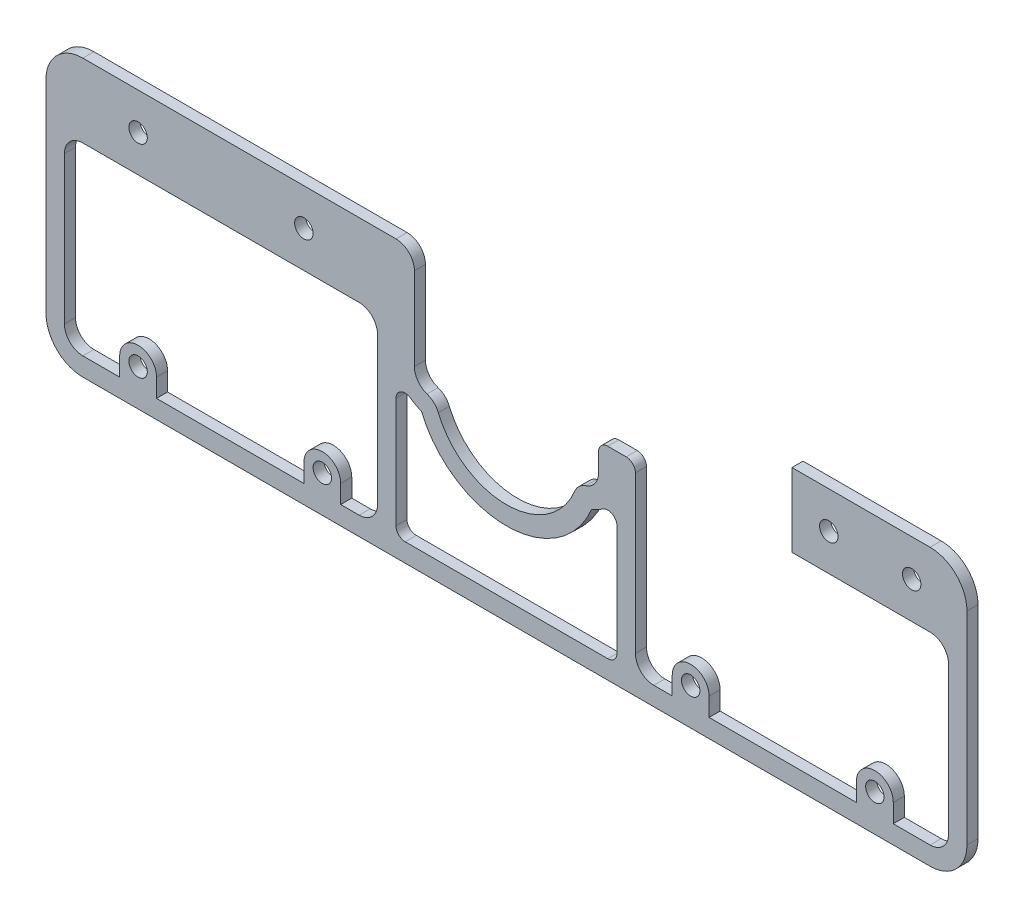
SolidWorks part; units mm, degrees
ref_plane "Front Plane" through (0, 0, 0) normal (0, 0, 1) x (1, 0, 0)
ref_plane "Top Plane" through (0, 0, 0) normal (0, 1, 0) x (1, 0, 0)
ref_plane "Right Plane" through (0, 0, 0) normal (1, 0, 0) x (0, 0, -1)
sketch "Sketch1" plane through (0, 0, 0) normal (0, 0, 1) x (1, 0, 0)
  line L0 (-40, 20) -> (-40, 55) construction
  line L4 (-250, -55) -> (-250, 3.1783)
  line L8 (-50, 75) -> (-230, 75) construction
  line L17 (0, -20) -> (0, -40)
  line L25 (0, -65) -> (0, -75)
  line L26 (0, 75) -> (0, -75) construction
  line L27 (-50, 95) -> (50, 95) construction
  line L34 (0, -75) -> (-230, -75)
  line L156 (-50, 75) -> (-230, 75) construction
  line L161 (0, -40) -> (0, -65)
  line L165 (-164.3309, 75) -> (-60, 75)
  line L167 (-230, 75) -> (-220, 75)
  line L171 (-250, 3.1783) -> (-250, 55)
  line L172 (-220, 75) -> (-164.3309, 75)
  line L173 (-50, 65) -> (-50, 20)
  arc A0 (-40, 20) -> (0, -20) centre (0, 20) ccw construction
  circle A1 centre (0, 20) radius 30 construction
  arc A4 (-230, -75) -> (-250, -55) centre (-230, -55) cw
  arc A5 (-250, 55) -> (-230, 75) centre (-230, 55) cw
  arc A124 (0, -20) -> (-37, 4.8013) centre (0, 20) cw
  arc A125 (-60, 75) -> (-50, 65) centre (-60, 65) cw
  arc A126 (-43.125, 10.5008) -> (-50, 20) centre (-40, 20) cw
  arc A127 (-37, 4.8013) -> (-43.125, 10.5008) centre (-46.25, 1.0016) ccw
  point P0 (0, 0)
  point P10 (-50, 10)
  point P11 (0, 50)
  point P30 (-40, 75)
  point P45 (0, -30)
  point P74 (0, 95)
  dimension "D3" = 80
  dimension "D4" = 60
  dimension "D6" = 55
  dimension "D7" = 75
  dimension "D10" = 10
  dimension "D11" = 20
  dimension "D8" = 10
  dimension "D5" = 10
  dimension "D9" = 20
  dimension "D13" = 210
  dimension "D16" = 100
  dimension "D17" = 20
  dimension "D26" = 250
extrude "Boss-Extrude1" add sketch "Sketch1" along normal blind 6
mirror "Mirror1" about plane through (0, -20, 6) normal (-1, 0, 0) of "Boss-Extrude1"
sketch "Sketch3" plane through (0, 0, 6) normal (0, 0, 1) x (1, 0, 0)
  line L0 (155, 75) -> (155, 35)
  line L1 (60, 75) -> (230, 75) construction
  line L2 (155, 35) -> (50, 35)
  line L3 (50, 20) -> (50, 65) construction
  line L4 (50, 20) -> (50, 65) construction
  line L5 (60, 75) -> (230, 75)
  line L6 (50, 65) -> (50, 35)
  line L7 (-60, 75) -> (-230, 75) construction
  line L8 (-250, 55) -> (-250, -55) construction
  line L9 (250, 55) -> (250, -55) construction
  arc A0 (60, 75) -> (50, 65) centre (60, 65) ccw construction
  arc A1 (60, 75) -> (50, 65) centre (60, 65) ccw
  circle A2 centre (175, 55) radius 5
  circle A3 centre (220, 55) radius 5
  circle A4 centre (-200, 55) radius 5
  circle A5 centre (-110, 55) radius 5
  line M15 (230, 75) -> (60, 75)
  arc M16 (60, 75) -> (50, 65) centre (60, 65) ccw
  line M17 (50, 65) -> (50, 20)
  dimension "D3" = 10
  dimension "D4" = 10
  dimension "D5" = 10
  dimension "D6" = 10
  dimension "D8" = 20
  dimension "D11" = 20
  dimension "D12" = 30
  dimension "D1" = 40
  dimension "D2" = 105
  dimension "D7" = 20
  dimension "D9" = 50
  dimension "D10" = 140
extrude "Cut-Extrude1" cut sketch "Sketch3" against normal through all contours L2 L0 M15 M16 M17 | A2 | A3 | A5 | A4
sketch "Sketch4" plane through (0, 0, 6) normal (0, 0, 1) x (1, 0, 0)
  line L0 (-230, -75) -> (230, -75) construction
  line L1 (-70, 25.101) -> (-70, -54.899)
  line L2 (-50, 20) -> (-50, 65) construction
  line L7 (-240, -55) -> (-240, 25.101)
  line L8 (-250, 55) -> (-250, -55) construction
  line L11 (-110, 35.101) -> (-80, 35.101)
  line L12 (-110, 35.101) -> (-140, 35.101)
  line L13 (-230, 35.101) -> (-140, 35.101)
  line L15 (-230, -65) -> (-210, -65)
  line L16 (-210, -65) -> (-210, -55)
  line L17 (-190, -55) -> (-190, -65)
  line L18 (-190, -65) -> (-110, -65)
  line L19 (-110, -65) -> (-110, -55)
  line L20 (-90, -55) -> (-90, -64.899)
  line L21 (-90, -64.899) -> (-80, -64.899)
  circle A1 centre (-200, -55) radius 5
  circle A2 centre (-100, -55) radius 5
  arc A6 (-230, -65) -> (-240, -55) centre (-230, -55) cw
  arc A12 (-210, -55) -> (-190, -55) centre (-200, -55) cw
  arc A13 (-110, -55) -> (-90, -55) centre (-100, -55) cw
  arc A14 (-240, 25.101) -> (-230, 35.101) centre (-230, 25.101) cw
  arc A15 (-70, -54.899) -> (-80, -64.899) centre (-80, -54.899) cw
  arc A16 (-70, 25.101) -> (-80, 35.101) centre (-80, 25.101) ccw
  point P0 (0, -75)
  point P1 (0, 0)
  point P10 (0, 0)
  point P12 (-240, 34.0787)
  point P15 (0, 0)
  point P27 (-240, 35.101)
  dimension "D13" = 10
  dimension "D17" = 10
  dimension "D2" = 10
  dimension "D3" = 200
  dimension "D4" = 100
  dimension "D7" = 20
  dimension "D9" = 10
  dimension "D11" = 20
  dimension "D16" = 80
extrude "Cut-Extrude2" cut sketch "Sketch4" against normal through all
mirror "Mirror2" about plane through (0, 0, 0) normal (1, 0, 0) of "Cut-Extrude2"
fillet "Fillet4" radius 5 1 edges at (50, 35, 3)
sketch "Sketch8" plane through (0, 0, 6) normal (0, 0, 1) x (1, 0, 0)
  line L0 (-60, 0) -> (-60, -64.899)
  line L2 (-60, -64.899) -> (60, -64.899)
  line L3 (60, -64.899) -> (60, 0)
  line L4 (-90, -64.899) -> (-80, -64.899) construction
  arc A0 (43.125, 10.5008) -> (50, 20) centre (40, 20) ccw construction
  arc A1 (43.125, 10.5008) -> (37, 4.8013) centre (46.25, 1.0016) ccw construction
  arc A2 (-37, 4.8013) -> (-43.125, 10.5008) centre (-46.25, 1.0016) ccw construction
  arc A3 (-50, 20) -> (-43.125, 10.5008) centre (-40, 20) ccw construction
  arc A4 (-37, 4.8013) -> (37, 4.8013) centre (0, 20) ccw construction
  arc A5 (43.125, 10.5008) -> (50, 20) centre (40, 20) ccw construction
  arc A6 (43.125, 10.5008) -> (37, 4.8013) centre (46.25, 1.0016) ccw construction
  arc A7 (-37, 4.8013) -> (-43.125, 10.5008) centre (-46.25, 1.0016) ccw construction
  arc A8 (-50, 20) -> (-43.125, 10.5008) centre (-40, 20) ccw construction
  arc A9 (-37, 4.8013) -> (37, 4.8013) centre (0, 20) ccw construction
  arc A10 (-52, 4) -> (-46.25, 1.0016) centre (-40, 20) ccw
  arc A11 (-46.25, 1.0016) -> (-46.25, 1.0016) centre (-46.25, 1.0016) ccw
  arc A12 (-46.25, 1.0016) -> (46.25, 1.0016) centre (0, 20) ccw
  arc A13 (46.25, 1.0016) -> (46.25, 1.0016) centre (46.25, 1.0016) ccw
  arc A14 (46.25, 1.0016) -> (52, 4) centre (40, 20) ccw
  arc A15 (46.25, 1.0016) -> (60, 20) centre (40, 20) ccw construction
  arc A16 (60, 0) -> (52, 4) centre (55, 0) ccw
  arc A17 (-60, 20) -> (-46.25, 1.0016) centre (-40, 20) ccw construction
  arc A18 (-60, 0) -> (-52, 4) centre (-55, 0) cw
  dimension "D2" = 5
  dimension "D1" = 10
extrude "Cut-Extrude5" cut sketch "Sketch8" against normal through all
fillet "Fillet5" radius 5 1 edges at (-60, -64.899, 3)
fillet "Fillet6" radius 5 1 edges at (60, -64.899, 3)
sketch "Sketch9" plane through (0, 0, 6) normal (0, 0, 1) x (1, 0, 0)
  line L0 (78.5825, 35) -> (55, 35) construction
  line L1 (78.5825, 35) -> (70, 35)
  line L2 (70, 25.101) -> (70, 35)
  arc A0 (78.5825, 35) -> (70, 25.101) centre (80, 25.101) ccw construction
  arc A1 (78.5825, 35) -> (70, 25.101) centre (80, 25.101) ccw
extrude "Cut-Extrude6" cut sketch "Sketch9" against normal through all
fillet "Fillet7" radius 5 1 edges at (70, 35, 3)
